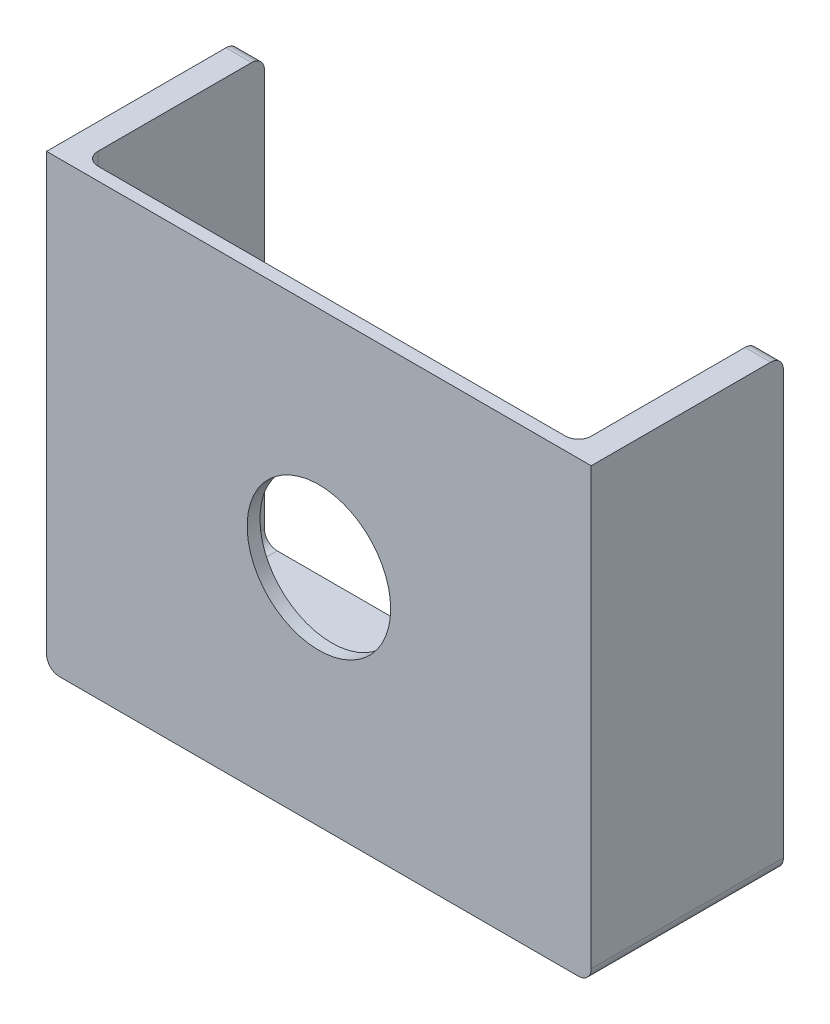
SolidWorks part; units mm, degrees
material "ABS"
ref_plane "Front Plane" through (0, 0, 0) normal (0, 0, 1) x (1, 0, 0)
ref_plane "Top Plane" through (0, 0, 0) normal (0, 1, 0) x (1, 0, 0)
ref_plane "Right Plane" through (0, 0, 0) normal (1, 0, 0) x (0, 0, -1)
sketch "Sketch1" plane through (0, 0, 0) normal (0, 0, 1) x (1, 0, 0)
  line L1 (0, 0) -> (85, 0)
  line L2 (0, 0) -> (0, 70)
  line L3 (0, 70) -> (85, 70)
  line L4 (85, 0) -> (85, 70)
  dimension "D1" = 70
  dimension "D2" = 85
extrude "Boss-Extrude1" add sketch "Sketch1" along normal blind 2
hole_wizard "Hole1" positions "Sketch2" profile "Sketch4" legacy end condition up to next
sketch "Sketch2" plane through (0, 0, 2) normal (0, 0, 1) x (1, 0, 0)
  line L0 (42.5, 35) -> (42.5, 0) construction
  line L1 (0, 0) -> (85, 0) construction
  point P0 (42.5, 35)
  dimension "D1" = 35
sketch "Sketch4" plane through (42.5, 35, 2) normal (1, 0, 0) x (0, -1, 0)
  line L0 (0, 0) -> (0, 2)
  line L1 (0, 2) -> (11.2, 2)
  line L2 (11.2, 2) -> (11.2, 0)
  line L3 (11.2, 0) -> (0, 0)
  line L4 (0, 110) -> (0, -10) construction
  dimension "Diameter" = 22.4
  dimension "Depth" = 2
sketch "Sketch5" plane through (85, 0, 0) normal (1, 0, 0) x (0, 0, -1)
  line L0 (-2, 0) -> (-2, 70) construction
  line L1 (0, 0) -> (28, 0)
  line L2 (0, 0) -> (0, 4)
  line L3 (0, 4) -> (28, 4)
  line L4 (28, 0) -> (28, 4)
  dimension "D1" = 4
  dimension "D2" = 30
extrude "Boss-Extrude2" add sketch "Sketch5" against normal up to surface (85 mm away) up to face at (0, 35, 1)
sketch "Sketch6" plane through (0, 70, 0) normal (0, 1, 0) x (1, 0, 0)
  line L0 (0, 28) -> (85, 28) construction
  line L1 (0, 0) -> (4, 0)
  line L2 (0, 0) -> (0, 28)
  line L3 (0, 28) -> (4, 28)
  line L4 (4, 0) -> (4, 28)
  line L5 (85, 0) -> (0, 0) construction
  line L6 (85, 0) -> (81, 0)
  line L7 (85, 0) -> (85, 28)
  line L8 (85, 28) -> (81, 28)
  line L9 (81, 0) -> (81, 28)
  line L10 (85, -2) -> (85, 0) construction
  line M6 (85, 0) -> (0, 0)
  dimension "D1" = 4
extrude "Boss-Extrude3" add sketch "Sketch6" against normal up to next contours L9 L7 L8 M6 | L4 L3 L2 M6
hole_wizard "M4 Clearance Hole1" positions "Sketch9" profile "Sketch11" hole size "M4" standard "DIN" end condition up to next
sketch "Sketch9" plane through (0, 4, 0) normal (0, 1, 0) x (1, 0, 0)
  line L0 (42.5, 28) -> (42.5, 0) construction
  line L1 (4, 28) -> (81, 28) construction
  line L2 (81, 0) -> (4, 0) construction
  line L4 (85, -2) -> (0, -2) construction
  point P0 (15, 13)
  point P2 (70, 13)
  dimension "D1" = 15
  dimension "D2" = 55
sketch "Sketch11" plane through (15, 4, -13) normal (1, 0, 0) x (0, 0, 1)
  line L0 (0, 0) -> (0, 4)
  line L1 (0, 4) -> (2.4, 4)
  line L2 (2.4, 4) -> (2.4, 0)
  line L5 (2.4, 0) -> (0, 0)
  line L11 (0, -6.35) -> (0, 107.95) construction
  dimension "Thru Hole Dia." = 4.8
  dimension "Thru Hole Depth" = 4
fillet "Fillet1" radius 2 9 edges at (85, 0, -13) (0, 0, -13) (2, 70, -28) (83, 70, -28) (81, 37, 0) (4, 37, 0) (4, 4, -14) (42.5, 4, 0) (81, 4, -14)
